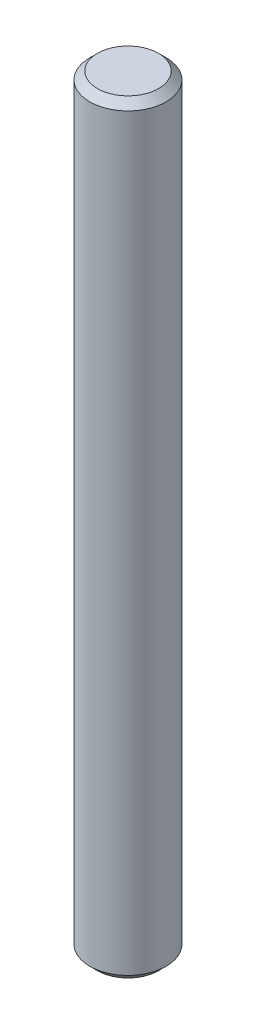
SolidWorks part; units mm, degrees
ref_plane "Front Plane" through (0, 0, 0) normal (0, 0, 1) x (1, 0, 0)
ref_plane "Top Plane" through (0, 0, 0) normal (0, 1, 0) x (1, 0, 0)
ref_plane "Right Plane" through (0, 0, 0) normal (1, 0, 0) x (0, 0, -1)
sketch "Sketch1" plane through (0, 0, 0) normal (0, 1, 0) x (1, 0, 0)
  circle A0 centre (0, 0) radius 5
  dimension "D1" = 10
extrude "Boss-Extrude1" add sketch "Sketch1" along normal blind 100
chamfer "Chamfer1" distance 1 angle 45 2 edges at (0, 0, 5) (0, 100, 5)
